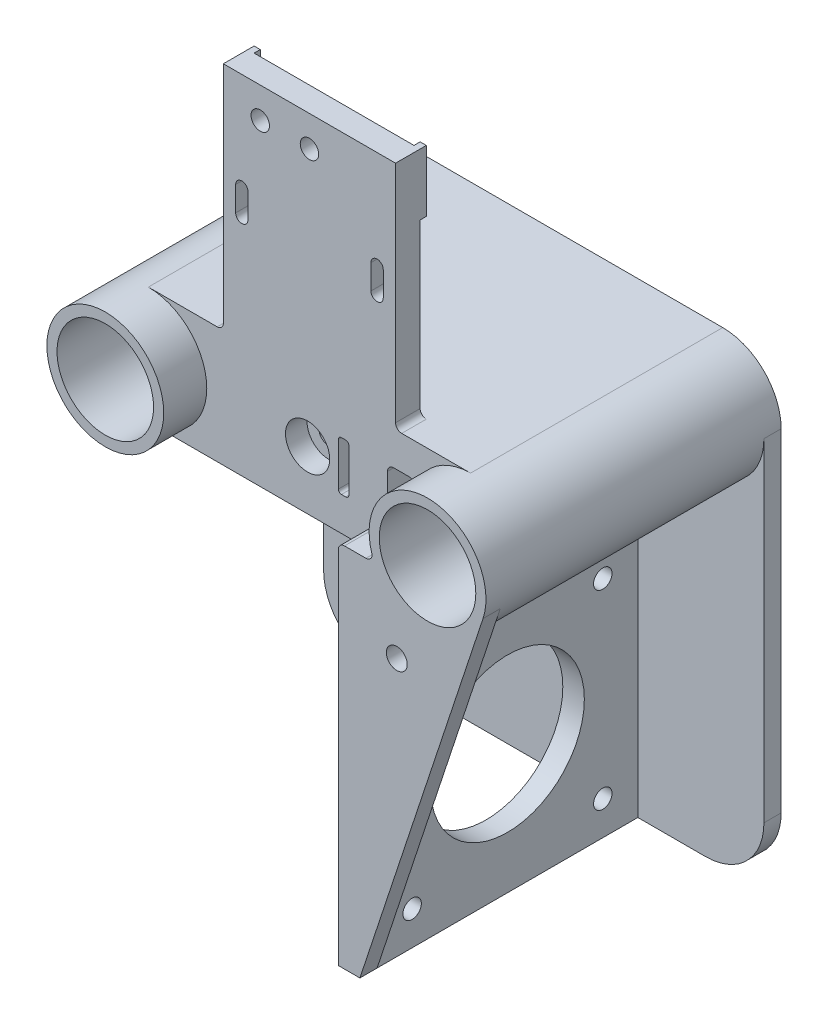
SolidWorks part; units mm, degrees
material "PET"
ref_plane "Front Plane" through (0, 0, 0) normal (0, 0, 1) x (1, 0, 0)
ref_plane "Top Plane" through (0, 0, 0) normal (0, 1, 0) x (1, 0, 0)
ref_plane "Right Plane" through (0, 0, 0) normal (1, 0, 0) x (0, 0, -1)
sketch "Sketch1" plane through (0, 0, 0) normal (0, 0, 1) x (1, 0, 0)
  circle A14 centre (0, 0) radius 7.85
  circle A15 centre (52.4, 0) radius 7.85
  circle A16 centre (0, 0) radius 9.5
  circle A17 centre (52.4, 0) radius 9.5
extrude "Boss-Extrude1" add sketch "Sketch1" along normal blind 48
sketch "Sketch29" plane through (0, 0, 0) normal (0, 0, -1) x (-1, 0, 0)
  line L6 (-52.4, 9.5) -> (0, 9.5)
  line L43 (-38.9, 3) -> (-38.9, -3)
  line L45 (9.5, -54.1) -> (9.5, 0)
  line L46 (-39.9, 4) -> (-42.3861, 4)
  line L47 (-39.9, -4) -> (-42.3861, -4)
  line L61 (0, -63.6) -> (-52.4, -63.6)
  line L62 (-61.9, -54.1) -> (-61.9, 0)
  arc A2 (-43.3861, 3) -> (-52.4, 9.5) centre (-52.4, 0) ccw
  arc A48 (-38.9, -3) -> (-39.9, -4) centre (-39.9, -3) cw
  arc A49 (-42.3861, -4) -> (-43.3861, -3) centre (-42.3861, -3) cw
  arc A50 (-42.3861, 4) -> (-43.3861, 3) centre (-42.3861, 3) ccw
  arc A51 (-39.9, 4) -> (-38.9, 3) centre (-39.9, 3) cw
  circle A58 centre (-3.3, -36.55) radius 1.5
  circle A59 centre (-17.3, -36.55) radius 1.5
  arc A61 (-61.9, -54.1) -> (-52.4, -63.6) centre (-52.4, -54.1) ccw
  arc A62 (0, -63.6) -> (9.5, -54.1) centre (0, -54.1) ccw
  arc A65 (0, 9.5) -> (9.5, 0) centre (0, 0) ccw
  arc A66 (-43.3861, -3) -> (-61.9, 0) centre (-52.4, 0) cw
extrude "Boss-Extrude18" add sketch "Sketch29" against normal blind 3
sketch "Sketch36" plane through (0, 0, 3) normal (0, 0, 1) x (1, 0, 0)
  line L1 (0, 9.5) -> (52.4, 9.5)
  line L2 (0, -9.5) -> (52.4, -9.5)
  line L3 (38.9, 3) -> (38.9, -3)
  line L4 (39.9, -4) -> (42.3861, -4)
  line L5 (39.9, 4) -> (42.3861, 4)
  line L11 (31.4, 4) -> (32.1, 4)
  line L12 (30.9, 3.5) -> (30.9, -3.5)
  line L13 (31.4, -4) -> (32.1, -4)
  line L14 (32.6, 3.5) -> (32.6, -3.5)
  arc A0 (0, 9.5) -> (0, -9.5) centre (0, 0) cw
  arc A2 (52.4, 9.5) -> (43.3861, 3) centre (52.4, 0) ccw
  arc A4 (39.9, 4) -> (38.9, 3) centre (39.9, 3) ccw
  arc A7 (42.3861, 4) -> (43.3861, 3) centre (42.3861, 3) cw
  arc A8 (42.3861, -4) -> (43.3861, -3) centre (42.3861, -3) ccw
  arc A9 (38.9, -3) -> (39.9, -4) centre (39.9, -3) ccw
  arc A11 (43.3861, -3) -> (52.4, -9.5) centre (52.4, 0) ccw
  arc A20 (32.1, -4) -> (32.6, -3.5) centre (32.1, -3.5) ccw
  arc A21 (30.9, -3.5) -> (31.4, -4) centre (31.4, -3.5) ccw
  arc A22 (32.1, 4) -> (32.6, 3.5) centre (32.1, 3.5) cw
  arc A23 (31.4, 4) -> (30.9, 3.5) centre (31.4, 3.5) ccw
  circle A24 centre (25.9, 0) radius 1.7
extrude "Boss-Extrude26" add sketch "Sketch36" along normal blind 38
sketch "Sketch14" plane through (0, -9.5, 0) normal (0, -1, 0) x (1, 0, 0)
  circle A2 centre (14.4, 28.5) radius 4.125
extrude "Boss-Extrude27" add sketch "Sketch14" along normal blind 4
sketch "Sketch34" plane through (0, 9.5, 0) normal (0, 1, 0) x (1, 0, 0)
  circle A4 centre (14.4, -28.5) radius 4.2
extrude "Cut-Extrude17" cut sketch "Sketch34" against normal blind 4.5
sketch "Sketch38" plane through (0, 5, 0) normal (0, 1, 0) x (1, 0, 0)
  circle A2 centre (14.5, -28.5) radius 2.15
extrude "Cut-Extrude18" cut sketch "Sketch38" against normal up to surface (18.5 mm away) up to face at (18.525, -13.5, 28.5)
sketch "Sketch39" plane through (0, 0, 3) normal (0, 0, 1) x (1, 0, 0)
  line L12 (41.4, -63.6) -> (37.9, -63.6)
  line L13 (37.9, -5) -> (37.9, -63.6)
  line L17 (41.4, -63.6) -> (41.4, -9.5)
  line L19 (38.9, -4) -> (42.3861, -4)
  line L20 (41.4, -9.5) -> (52.4, -9.5)
  arc A2 (37.9, -5) -> (38.9, -4) centre (38.9, -5) cw
  arc A3 (42.3861, -4) -> (43.3861, -3) centre (42.3861, -3) ccw
  arc A5 (43.3861, -3) -> (52.4, -9.5) centre (52.4, 0) ccw
  point P13 (42.3009, -4)
  point P16 (0, 0)
extrude "Boss-Extrude43" add sketch "Sketch39" along normal offset from surface (42.2 mm away) 2.8 up to face at (61.9, 0, 48)
sketch "Sketch7" plane through (0, 0, 45.2) normal (0, 0, 1) x (1, 0, 0)
  line L1 (38.9, -4) -> (42.3861, -4)
  line L3 (37.9, -5) -> (37.9, -63.6)
  line L9 (41.4, -63.6) -> (61.4208, -2.9792)
  line L12 (37.9, -63.6) -> (41.4, -63.6)
  arc A3 (61.4208, -2.9792) -> (43.3861, -3) centre (52.4, 0) cw
  arc A7 (43.3861, -3) -> (42.3861, -4) centre (42.3861, -3) cw
  arc A9 (38.9, -4) -> (37.9, -5) centre (38.9, -5) ccw
  circle A12 centre (47.4, -15.6) radius 1.7
extrude "Boss-Extrude44" add sketch "Sketch7" along normal up to surface (2.8 mm away) up to face at (61.9, 0, 48)
sketch "Sketch69" plane through (37.9, 0, 0) normal (-1, 0, 0) x (0, 0, 1)
  line L0 (3, -9.5) -> (3, -25)
  line L2 (3, -25) -> (18.5, -9.5)
  line L4 (18.5, -9.5) -> (3, -9.5)
extrude "Boss-Extrude42" add sketch "Sketch69" along normal blind 6.5 from offset 25
sketch "Sketch40" plane through (0, 0, 45.2) normal (0, 0, -1) x (-1, 0, 0)
  line L23 (-42.2, -12.85) -> (-41.4, -12.85)
  line L24 (-42.2, -18.15) -> (-41.4, -18.15)
  line L26 (-41.4, -12.85) -> (-41.4, -18.15)
  line L28 (-42.7, -13.35) -> (-42.7, -17.65)
  arc A10 (-42.2, -12.85) -> (-42.7, -13.35) centre (-42.2, -13.35) ccw
  arc A11 (-42.7, -17.65) -> (-42.2, -18.15) centre (-42.2, -17.65) ccw
extrude "Boss-Extrude45" add sketch "Sketch40" along normal blind 10
sketch "Sketch47" plane through (41.4, 0, 0) normal (1, 0, 0) x (0, 0, -1)
  circle A0 centre (-8.5, -15.55) radius 1.5
  circle A1 centre (-8.5, -15.55) radius 4
extrude "Boss-Extrude40" add sketch "Sketch47" along normal blind 1.4
sketch "Sketch20" plane through (41.4, 0, 0) normal (1, 0, 0) x (0, 0, -1)
  circle A0 centre (-8.5, -58.1) radius 1.5
  circle A1 centre (-39.5, -58.1) radius 1.5
  circle A2 centre (-8.5, -27.1) radius 1.5
  circle A3 centre (-24, -42.6) radius 12.5
  circle A5 centre (-8.5, -15.55) radius 1.5
extrude "Cut-Extrude19" cut sketch "Sketch20" against normal up to surface (3.5 mm away) up to face at (37.9, -26.0333, 30.6667)
sketch "Sketch43" plane through (0, 0, 41) normal (0, 0, 1) x (1, 0, 0)
  circle A1 centre (25.9, 0) radius 3.6
extrude "Cut-Extrude22" cut sketch "Sketch43" against normal blind 3.5
sketch "Sketch59" plane through (0, 0, 41) normal (0, 0, 1) x (1, 0, 0)
  line L20 (11.2, 9.5) -> (41.2, 9.5)
  line L28 (12.2, 10.5) -> (12.2, 47.05)
  line L29 (12.2, 47.05) -> (40.2, 47.05)
  line L30 (40.2, 47.05) -> (40.2, 10.5)
  arc A7 (11.2, 9.5) -> (12.2, 10.5) centre (11.2, 10.5) ccw
  arc A8 (40.2, 10.5) -> (41.2, 9.5) centre (41.2, 10.5) ccw
extrude "Boss-Extrude38" add sketch "Sketch59" against normal blind 4
sketch "Sketch52" plane through (-30, 0, 37) normal (0, 0, -1) x (-1, 0, 0)
  line L9 (-70.2, 47.05) -> (-69.2, 47.05)
  line L10 (-70.2, 47.05) -> (-70.2, 37.05)
  line L11 (-70.2, 37.05) -> (-69.2, 37.05)
  line L12 (-69.2, 47.05) -> (-69.2, 37.05)
  line L13 (-43.2, 47.05) -> (-42.2, 47.05)
  line L14 (-43.2, 47.05) -> (-43.2, 37.05)
  line L15 (-43.2, 37.05) -> (-42.2, 37.05)
  line L16 (-42.2, 47.05) -> (-42.2, 37.05)
extrude "Boss-Extrude36" add sketch "Sketch52" along normal blind 1
sketch "Sketch53" plane through (-30, 0, 37) normal (0, 0, -1) x (-1, 0, 0)
  line L15 (-68.2, 31.05) -> (-68.2, 27.05)
  line L17 (-66.2, 31.05) -> (-66.2, 27.05)
  line L29 (-46.2, 31.05) -> (-46.2, 27.05)
  line L30 (-44.2, 31.05) -> (-44.2, 27.05)
  circle A26 centre (-48.2, 42.05) radius 1.5
  circle A27 centre (-56.2, 42.05) radius 1.5
  arc A32 (-66.2, 31.05) -> (-68.2, 31.05) centre (-67.2, 31.05) ccw
  arc A33 (-68.2, 27.05) -> (-66.2, 27.05) centre (-67.2, 27.05) ccw
  arc A34 (-44.2, 31.05) -> (-46.2, 31.05) centre (-45.2, 31.05) ccw
  arc A35 (-46.2, 27.05) -> (-44.2, 27.05) centre (-45.2, 27.05) ccw
extrude "Cut-Extrude29" cut sketch "Sketch53" against normal up to surface (4 mm away) up to face at (29.5, 0, 41)
sketch "Sketch62" plane through (0, 0, 3) normal (0, 0, 1) x (1, 0, 0)
  line L4 (61.9, -54.1) -> (61.9, 0)
  line L5 (52.4, -63.6) -> (41.4, -63.6)
  line L6 (41.4, -63.6) -> (41.4, -9.5)
  line L7 (41.4, -9.5) -> (52.4, -9.5)
  arc A1 (52.4, -9.5) -> (61.9, 0) centre (52.4, 0) ccw
  arc A2 (52.4, -63.6) -> (61.9, -54.1) centre (52.4, -54.1) ccw
extrude "Cut-Extrude30" cut sketch "Sketch62" against normal blind 0.2
sketch "Sketch70" plane through (0, 0, 0) normal (0, 0, -1) x (-1, 0, 0)
  line L2 (-33.9, -6.5) -> (-22.9, -6.5)
  line L3 (-20.9, -4.5) -> (-20.9, 4.5)
  line L4 (-22.9, 6.5) -> (-33.9, 6.5)
  line L5 (-35.9, 4.5) -> (-35.9, -4.5)
  arc A0 (-35.9, 4.5) -> (-33.9, 6.5) centre (-33.9, 4.5) cw
  arc A2 (-22.9, 6.5) -> (-20.9, 4.5) centre (-22.9, 4.5) cw
  arc A4 (-20.9, -4.5) -> (-22.9, -6.5) centre (-22.9, -4.5) cw
  arc A7 (-33.9, -6.5) -> (-35.9, -4.5) centre (-33.9, -4.5) cw
extrude "Cut-Extrude33" cut sketch "Sketch70" against normal blind 25
sketch "Sketch66" plane through (0, 0, 25) normal (0, 0, -1) x (-1, 0, 0)
  line L1 (-31.4, 4) -> (-32.9, 4)
  line L2 (-30.9, 3.5) -> (-30.9, -3.5)
  line L3 (-31.4, -4) -> (-32.9, -4)
  line L4 (-33.4, 3.5) -> (-33.4, -3.5)
  arc A0 (-30.9, -3.5) -> (-31.4, -4) centre (-31.4, -3.5) cw
  arc A1 (-32.9, -4) -> (-33.4, -3.5) centre (-32.9, -3.5) cw
  arc A2 (-32.9, 4) -> (-33.4, 3.5) centre (-32.9, 3.5) ccw
  arc A3 (-31.4, 4) -> (-30.9, 3.5) centre (-31.4, 3.5) cw
extrude "Cut-Extrude32" cut sketch "Sketch66" against normal blind 8
